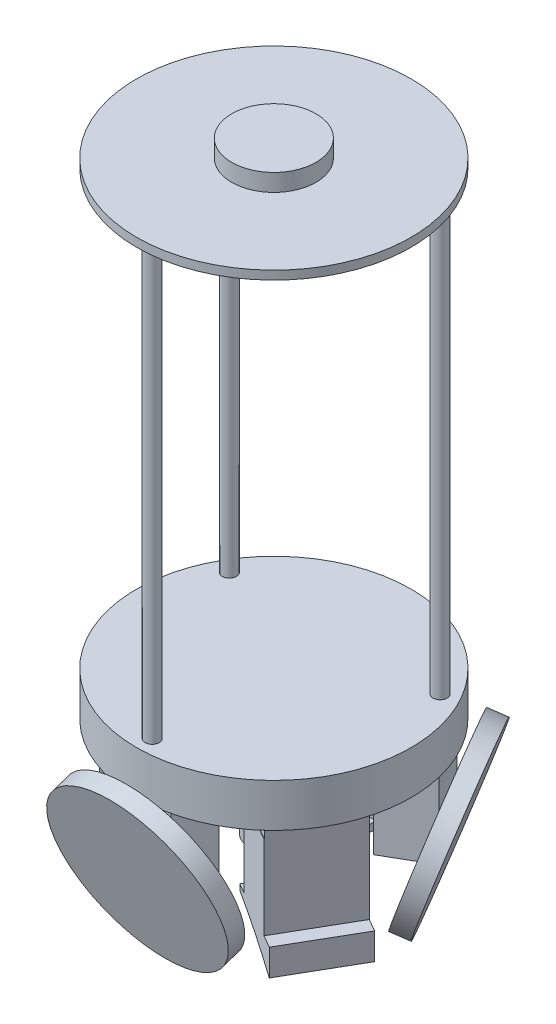
SolidWorks part; units mm, degrees
ref_plane "前视基准面" through (0, 0, 0) normal (0, 0, 1) x (1, 0, 0)
ref_plane "上视基准面" through (0, 0, 0) normal (0, 1, 0) x (1, 0, 0)
ref_plane "右视基准面" through (0, 0, 0) normal (1, 0, 0) x (0, 0, -1)
sketch "草图2" plane through (0, 0, 0) normal (0, 1, 0) x (1, 0, 0)
  circle A0 centre (0, 0) radius 31.6898
extrude "凸台-拉伸1" add sketch "草图2" along normal blind 10
sketch "草图3" plane through (0, 0, 0) normal (0, -1, 0) x (1, 0, 0)
  line L0 (5.6993, 29.3987) -> (5.6993, 18.3801)
  line L1 (-5.6993, 29.3987) -> (5.6993, 29.3987)
  line L2 (-5.6993, 29.3987) -> (-5.6993, 18.3801)
  line L3 (-5.6993, 18.3801) -> (5.6993, 18.3801)
extrude "凸台-拉伸2" add sketch "草图3" along normal blind 20
sketch "草图4" plane through (5.6993, 0, 0) normal (1, 0, 0) x (0, 0, -1)
  line L0 (-29.3987, -10) -> (-26.0569, -20)
  line L1 (-29.3987, -20) -> (-29.3987, 0) construction
  line L2 (-18.3801, -20) -> (-29.3987, -20) construction
  line L3 (-26.0569, -20) -> (-29.3987, -20)
  line L4 (-29.3987, -20) -> (-29.3987, -10)
extrude "切除-拉伸1" cut sketch "草图4" against normal blind 20
sketch "草图5" plane through (0, 0, 0) normal (0, 0, 1) x (1, 0, 0)
  line L0 (0, 15.295) -> (0, -30.6532) construction
sketch "草图6" plane through (0, -9.8422, 29.4515) normal (0, -0.317, 0.9484) x (1, 0, 0)
  line L0 (0, 14.5064) -> (0, -29.0727) construction
  circle A0 centre (0, -5.5788) radius 20
extrude "凸台-拉伸3" add sketch "草图6" along normal blind 4
pattern_circular "阵列(圆周)2" count 3 every 120 about axis through (0, 0, 0) along (0, 1, 0) of "凸台-拉伸2", "切除-拉伸1", "凸台-拉伸3"
sketch "草图7" plane through (0, 0, 0) normal (0, -1, 0) x (1, 0, 0)
  line L0 (8.8677, 0) -> (8.8677, -27.0946)
  line L3 (8.8677, -27.0946) -> (-8.8677, -27.0946)
  line L4 (-8.8677, 0) -> (-8.8677, -27.0946)
  line L5 (-4.4339, -7.6797) -> (-27.8984, 5.8676)
  line L6 (-27.8984, 5.8676) -> (-19.0307, 21.227)
  line L7 (4.4339, 7.6797) -> (-19.0307, 21.227)
  line L8 (-4.4339, 7.6797) -> (19.0307, 21.227)
  line L9 (19.0307, 21.227) -> (27.8984, 5.8676)
  line L10 (4.4339, -7.6797) -> (27.8984, 5.8676)
  arc A0 (8.8677, 0) -> (-8.8677, 0) centre (0, 0) ccw
  arc A1 (-4.4339, -7.6797) -> (4.4339, 7.6797) centre (0, 0) ccw
  arc A2 (-4.4339, 7.6797) -> (4.4339, -7.6797) centre (0, 0) ccw
  point P17 (0, 0)
  dimension "D1" = 3
extrude "凸台-拉伸4" add sketch "草图7" along normal blind 4 contours A0 L8 L7 L6 L5 L4 | A0 L0 L10 L9 L8 L7 | A1 L5 L4 L3 L0 L10 | A0 A2 A1 | A1 L10 L0 | A2 L4 L5 | A0 L7 L8
sketch "草图8" plane through (4.4339, 0, -7.6797) normal (0.5, 0, -0.866) x (-0.866, 0, -0.5)
  line L0 (-30.4271, -29.4828) -> (-30.4271, -23.3259)
  line L1 (-27.0946, -4) -> (-14.617, -4)
  line L2 (-27.0946, -4) -> (-27.0946, -23.3259)
  line L4 (-14.617, -4) -> (-14.617, -23.3259)
  line L5 (-30.4271, -23.3259) -> (-27.0946, -23.3259)
  line L6 (-11.8475, -24.665) -> (-11.8475, -23.3259)
  line L7 (-11.8475, -23.3259) -> (-14.617, -23.3259)
  arc A0 (-30.4271, -29.4828) -> (-11.8475, -24.665) centre (0, -108.5902) cw
  dimension "D1" = 19.3259
extrude "凸台-拉伸5" add sketch "草图8" against normal blind 17.8
pattern_circular "阵列(圆周)3" count 3 every 120 about axis through (0, 0, 0) along (0, 1, 0) of "凸台-拉伸5"
sketch "草图9" plane through (0, -4, 0) normal (0, -1, 0) x (1, 0, 0)
  circle A0 centre (0, 0) radius 5.6251
extrude "凸台-拉伸6" add sketch "草图9" along normal blind 19 contours A0
sketch "草图10" plane through (0, 10, 0) normal (0, 1, 0) x (1, 0, 0)
  circle A0 centre (0, -28.0814) radius 1.6308
extrude "凸台-拉伸7" add sketch "草图10" along normal blind 100
pattern_circular "阵列(圆周)4" count 3 every 120 about axis through (0, 0, 0) along (0, 1, 0) of "凸台-拉伸7"
sketch "草图11" plane through (0, 110, 0) normal (0, 1, 0) x (1, 0, 0)
  circle A0 centre (0, 0) radius 31.6898
extrude "凸台-拉伸8" add sketch "草图11" along normal blind 2
sketch "草图12" plane through (0, 112, 0) normal (0, 1, 0) x (1, 0, 0)
  circle A0 centre (0, 0) radius 9.7246
extrude "凸台-拉伸9" add sketch "草图12" along normal blind 4
